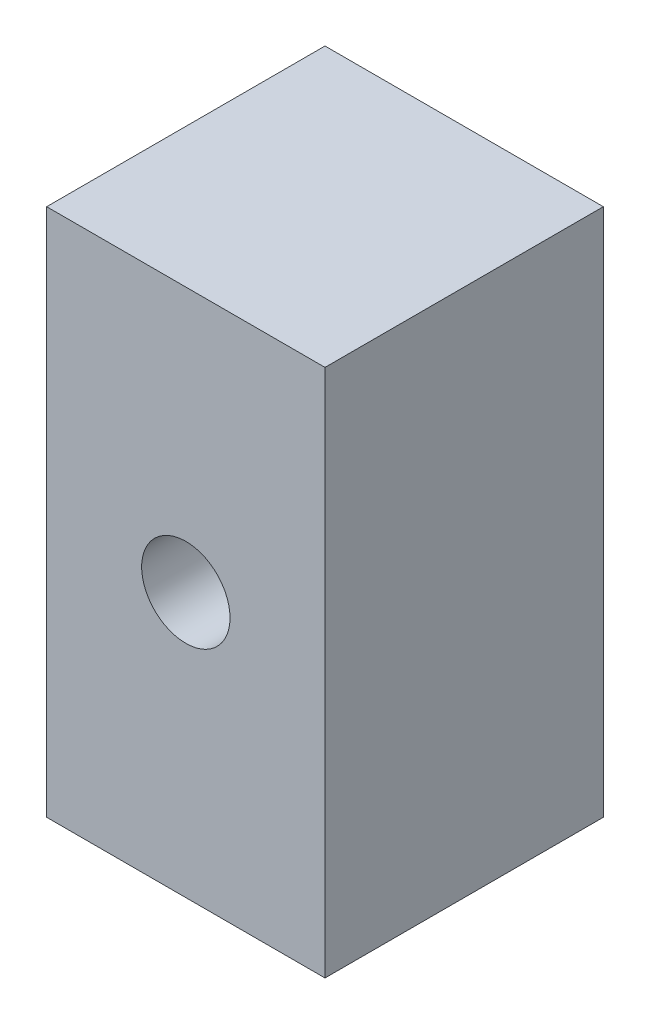
SolidWorks part; units mm, degrees
ref_plane "Front Plane" through (0, 0, 0) normal (0, 0, 1) x (1, 0, 0)
ref_plane "Top Plane" through (0, 0, 0) normal (0, 1, 0) x (1, 0, 0)
ref_plane "Right Plane" through (0, 0, 0) normal (1, 0, 0) x (0, 0, -1)
sketch "Sketch1" plane through (0, 0, 0) normal (0, 1, 0) x (1, 0, 0)
  line L1 (0, 0) -> (20, 0)
  line L2 (0, 0) -> (0, 20)
  line L3 (0, 20) -> (20, 20)
  line L4 (20, 0) -> (20, 20)
  dimension "D1" = 20
  dimension "D2" = 20
extrude "Boss-Extrude1" add sketch "Sketch1" along normal blind 38
sketch "Sketch2" plane through (0, 0, 0) normal (0, 0, 1) x (1, 0, 0)
  line L0 (0, 0) -> (20, 0) construction
  line L1 (20, 38) -> (20, 0) construction
  circle A0 centre (10, 19) radius 3.175
  point P0 (10, 0)
  point P1 (20, 19)
  point P4 (10, 19)
  dimension "D1" = 6.35
extrude "Cut-Extrude1" cut sketch "Sketch2" against normal blind 38
